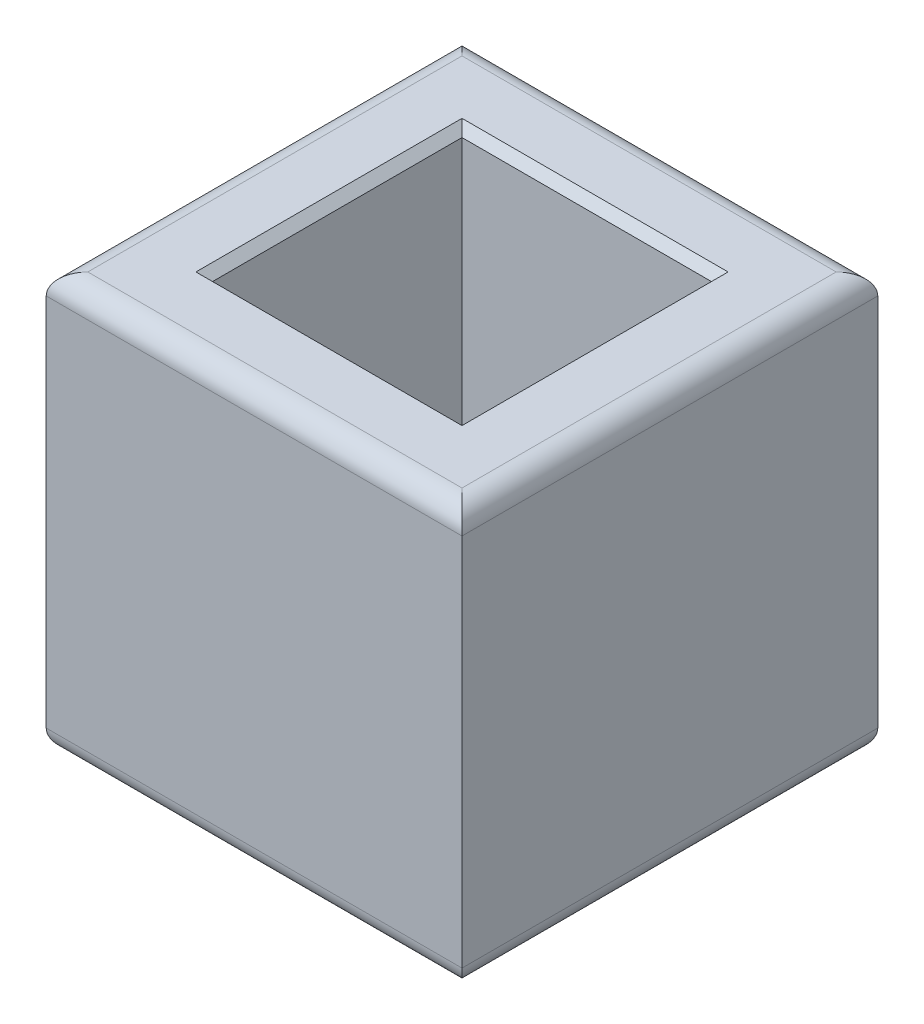
SolidWorks part; units mm, degrees
ref_plane "Front Plane" through (0, 0, 0) normal (0, 0, 1) x (1, 0, 0)
ref_plane "Top Plane" through (0, 0, 0) normal (0, 1, 0) x (1, 0, 0)
ref_plane "Right Plane" through (0, 0, 0) normal (1, 0, 0) x (0, 0, -1)
sketch "Sketch1" plane through (0, 0, 0) normal (0, 1, 0) x (1, 0, 0)
  line L1 (-63.5, -63.5) -> (63.5, -63.5)
  line L2 (-63.5, -63.5) -> (-63.5, 63.5)
  line L3 (-63.5, 63.5) -> (63.5, 63.5)
  line L4 (63.5, -63.5) -> (63.5, 63.5)
  line L5 (-63.5, -63.5) -> (63.5, 63.5) construction
  line L6 (-63.5, 63.5) -> (63.5, -63.5) construction
  point P0 (0, 0)
  dimension "D1" = 127
extrude "Boss-Extrude1" add sketch "Sketch1" along normal blind 127
sketch "Sketch2" plane through (0, 127, 0) normal (0, 1, 0) x (1, 0, 0)
  line L1 (-38.1, -38.1) -> (38.1, -38.1)
  line L2 (-38.1, -38.1) -> (-38.1, 38.1)
  line L3 (-38.1, 38.1) -> (38.1, 38.1)
  line L4 (38.1, -38.1) -> (38.1, 38.1)
  line L5 (-38.1, -38.1) -> (38.1, 38.1) construction
  line L6 (-38.1, 38.1) -> (38.1, -38.1) construction
  point P0 (0, 0)
  dimension "D1" = 76.2
extrude "Cut-Extrude1" cut sketch "Sketch2" against normal through all
chamfer "Chamfer1" distance 2.54 angle 45 7 edges at (-38.1, 127, 0) (0, 127, 38.1) (38.1, 127, 0) (0, 127, -38.1) (0, 0, -38.1) (-38.1, 0, 0) (0, 0, 38.1)
fillet "Fillet1" radius 6.35 8 edges at (0, 127, 63.5) (-63.5, 127, 0) (0, 127, -63.5) (63.5, 127, 0) (-63.5, 0, 0) (0, 0, -63.5) (63.5, 0, 0) (0, 0, 63.5)
